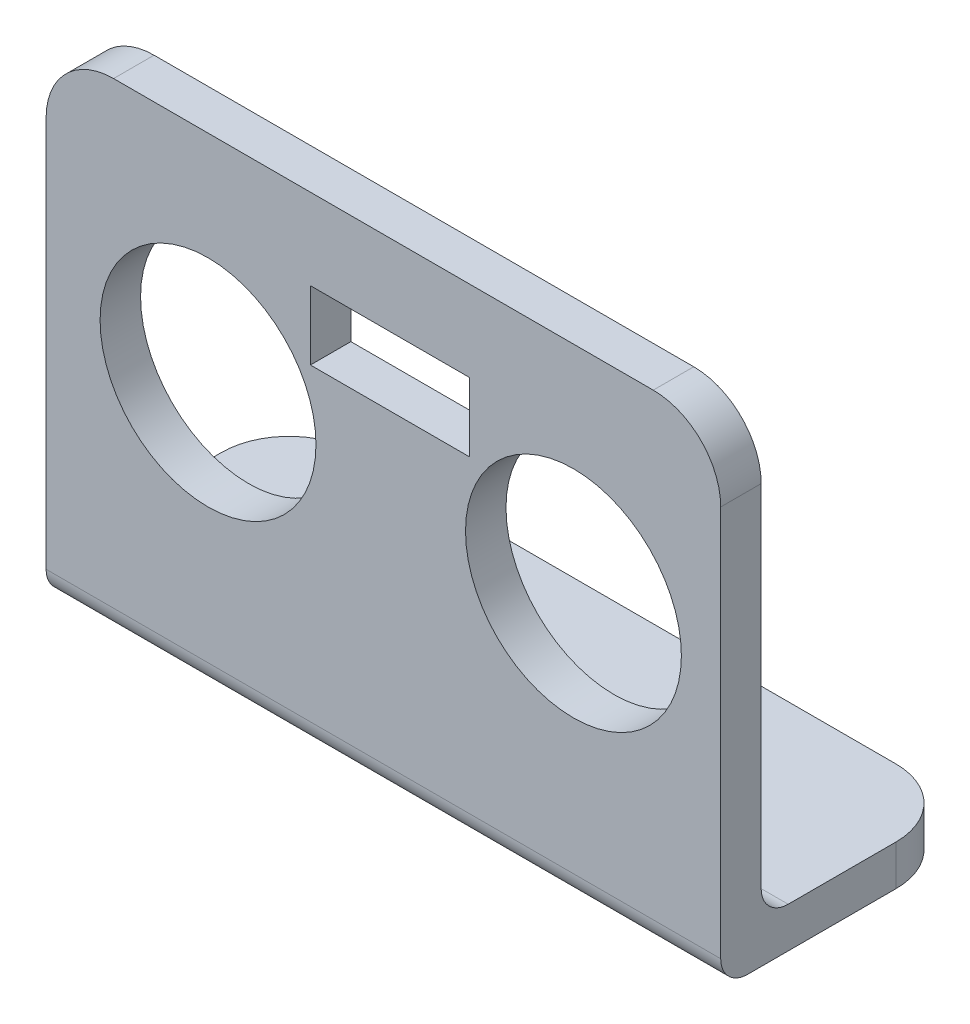
SolidWorks part; units mm, degrees
ref_plane "Front Plane" through (0, 0, 0) normal (0, 0, 1) x (1, 0, 0)
ref_plane "Top Plane" through (0, 0, 0) normal (0, 1, 0) x (1, 0, 0)
ref_plane "Right Plane" through (0, 0, 0) normal (1, 0, 0) x (0, 0, -1)
sketch "Sketch1" plane through (0, 0, 0) normal (0, 0, 1) x (1, 0, 0)
  line L0 (-5.4119, 30) -> (-5.4119, 24.9067)
  line L1 (-25, 0) -> (25, 0)
  line L2 (-25, 0) -> (-25, 36)
  line L3 (-25, 36) -> (25, 36)
  line L4 (25, 0) -> (25, 36)
  line L5 (23, 30) -> (-22, 30) construction
  line L6 (-5.4119, 24.9067) -> (6.3952, 24.9067)
  line L7 (6.3952, 24.9067) -> (6.3952, 30)
  line L8 (6.3952, 30) -> (-5.4119, 30)
  circle A0 centre (-13, 20) radius 8
  circle A1 centre (14.0849, 20) radius 8
  dimension "D3" = 16
  dimension "D4" = 27.0849
  dimension "D1" = 36
  dimension "D2" = 50
  dimension "D5" = 20
  dimension "D6" = 25
  dimension "D7" = 5.0933
  dimension "D8" = 18.6048
  dimension "D9" = 19.5881
extrude "Boss-Extrude1" add sketch "Sketch1" along normal blind 3
sketch "Sketch2" plane through (0, 0, 0) normal (0, 1, 0) x (1, 0, 0)
  line L0 (25, 0) -> (-25, 0) construction
  line L1 (-25, -3) -> (25, -3)
  line L2 (-25, -3) -> (-25, 15)
  line L3 (-25, 15) -> (25, 15)
  line L4 (25, -3) -> (25, 15)
  circle A0 centre (0, 7.5) radius 1.6
  circle A1 centre (-11, 7.5) radius 1.6
  circle A2 centre (11, 7.5) radius 1.6
  dimension "D1" = 3.2
  dimension "D2" = 14
  dimension "D3" = 25
  dimension "D4" = 36
  dimension "D5" = 10.5
  dimension "D6" = 11
  dimension "D7" = 11
  dimension "D8" = 15
extrude "Boss-Extrude2" add sketch "Sketch2" along normal blind 3
fillet "Fillet1" radius 5 4 edges at (25, 1.5, -15) (-25, 1.5, -15) (25, 36, 1.5) (-25, 36, 1.5)
fillet "Fillet2" radius 2 2 edges at (0, 3, 0) (0, 0, 3)
